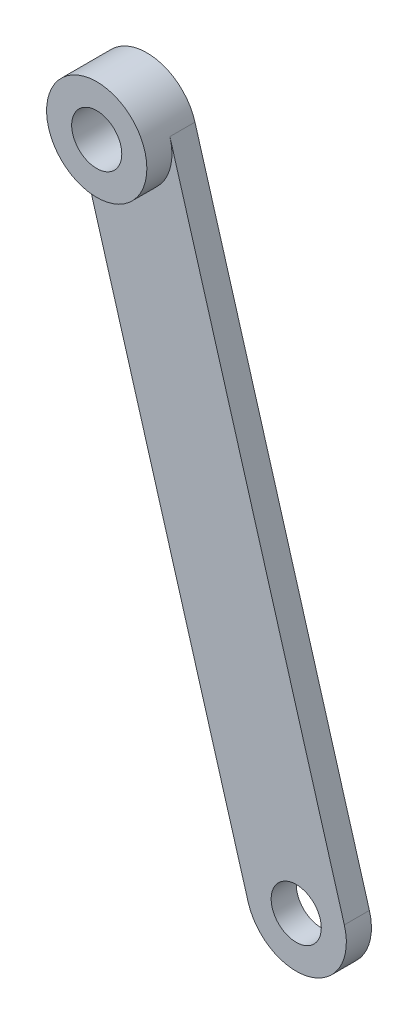
SolidWorks part; units mm, degrees
ref_plane "Front" through (0, 0, 0) normal (0, 0, 1) x (1, 0, 0)
ref_plane "Top" through (0, 0, 0) normal (0, 1, 0) x (1, 0, 0)
ref_plane "Right" through (0, 0, 0) normal (1, 0, 0) x (0, 0, -1)
sketch "Sketch1" plane through (0, 0, 0) normal (0, 0, 1) x (1, 0, 0)
  line L0 (-38, -7.8) -> (-26.9521, -45.5152) construction
  line L1 (-34.953, -6.9075) -> (-23.9051, -44.6226)
  line L2 (-41.047, -8.6925) -> (-29.9991, -46.4077)
  arc A0 (-34.953, -6.9075) -> (-41.047, -8.6925) centre (-38, -7.8) ccw
  arc A1 (-29.9991, -46.4077) -> (-23.9051, -44.6226) centre (-26.9521, -45.5152) ccw
  circle A2 centre (-26.9521, -45.5152) radius 1.5875
  circle A3 centre (-38, -7.8) radius 1.5875
  point P4 (-32.4761, -26.6576)
  dimension "D1" = 3.175
  dimension "D2" = 6.35
extrude "Boss-Extrude1" add sketch "Sketch1" along normal blind 1.5875
sketch "Sketch2" plane through (0, 0, 1.5875) normal (0, 0, 1) x (1, 0, 0)
  circle A0 centre (-38, -7.8) radius 1.5875 construction
  arc A1 (-34.953, -6.9075) -> (-41.047, -8.6925) centre (-38, -7.8) ccw construction
  circle A2 centre (-38, -7.8) radius 1.5875
  circle A3 centre (-38, -7.8) radius 3.175
extrude "Boss-Extrude2" add sketch "Sketch2" along normal blind 1.5875
